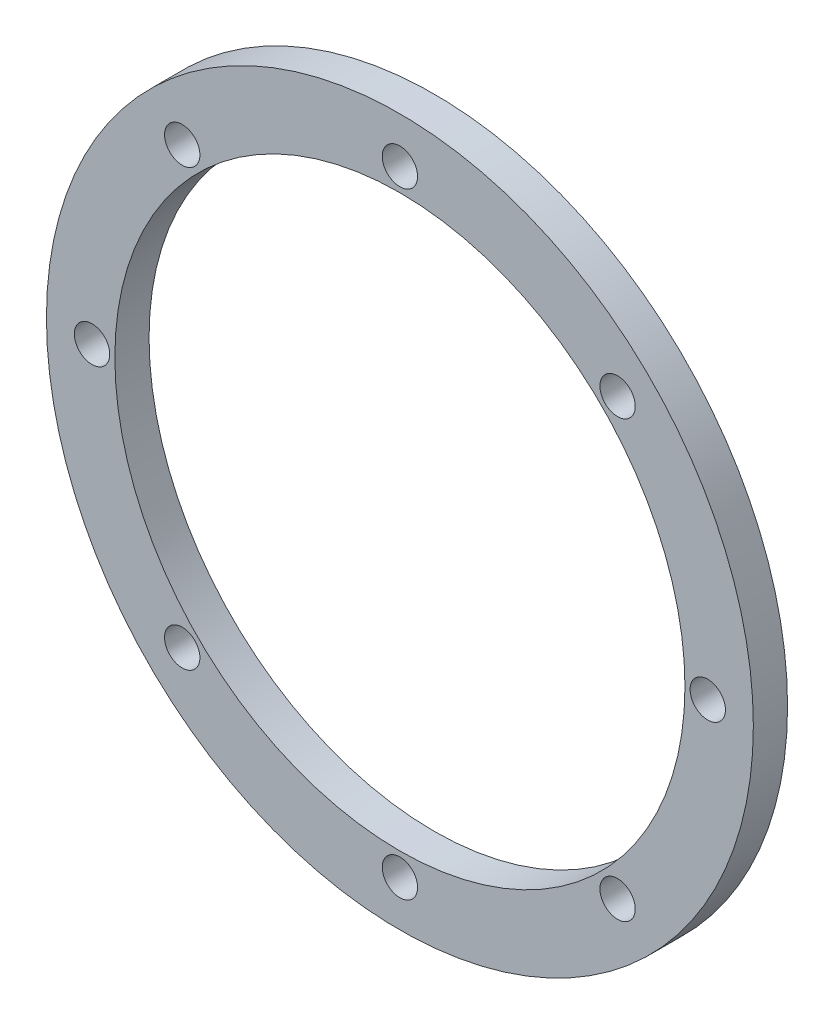
SolidWorks part; units mm, degrees
ref_plane "Front Plane" through (0, 0, 0) normal (0, 0, 1) x (1, 0, 0)
ref_plane "Top Plane" through (0, 0, 0) normal (0, 1, 0) x (1, 0, 0)
ref_plane "Right Plane" through (0, 0, 0) normal (1, 0, 0) x (0, 0, -1)
sketch "Sketch1" plane through (0, 0, 0) normal (0, 0, 1) x (1, 0, 0)
  circle A0 centre (0, 0) radius 27 construction
  circle A1 centre (-27, 0) radius 1.55
  circle A2 centre (-19.0919, 19.0919) radius 1.55
  circle A3 centre (0, 27) radius 1.55
  circle A4 centre (19.0919, 19.0919) radius 1.55
  circle A5 centre (27, 0) radius 1.55
  circle A6 centre (19.0919, -19.0919) radius 1.55
  circle A7 centre (0, -27) radius 1.55
  circle A8 centre (-19.0919, -19.0919) radius 1.55
  circle A9 centre (0, 0) radius 24 construction
  circle A10 centre (0, 0) radius 25
  circle A11 centre (0, 0) radius 31
  point P21 (0, 0)
  dimension "D1" = 8
extrude "Boss-Extrude1" add sketch "Sketch1" along normal blind 3
